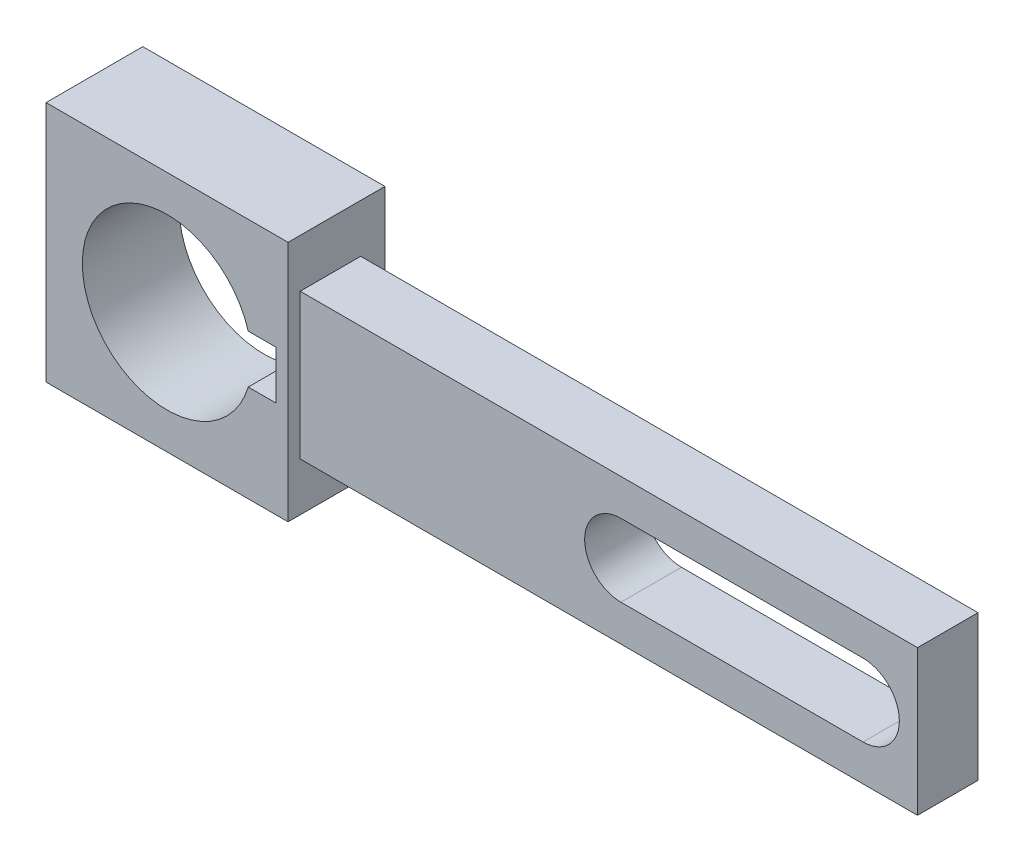
SolidWorks part; units mm, degrees
ref_plane "前视基准面" through (0, 0, 0) normal (0, 0, 1) x (1, 0, 0)
ref_plane "上视基准面" through (0, 0, 0) normal (0, 1, 0) x (1, 0, 0)
ref_plane "右视基准面" through (0, 0, 0) normal (1, 0, 0) x (0, 0, -1)
sketch "草图1" plane through (0, 0, 0) normal (0, 0, 1) x (1, 0, 0)
  line L0 (5, 2) -> (7, 0) construction
  line L9 (-10, -10) -> (10, -10)
  line L10 (-10, -10) -> (-10, 10)
  line L11 (-10, 10) -> (10, 10)
  line L12 (10, -10) -> (10, 10)
  line L13 (-10, -10) -> (10, 10) construction
  line L14 (-10, 10) -> (10, -10) construction
  line L15 (6.7082, -2) -> (9, -2)
  line L16 (5, -2) -> (5, 2) construction
  line L17 (6.7082, 2) -> (9, 2)
  line L18 (9, -2) -> (9, 2)
  line L19 (7, 0) -> (9, 2) construction
  line L20 (7, 0) -> (9, -2) construction
  line L21 (5, 2) -> (6.7082, 2) construction
  line L22 (5, -2) -> (7, 0) construction
  line L23 (5, -2) -> (6.7082, -2) construction
  arc A1 (6.7082, 2) -> (6.7082, -2) centre (0, 0) ccw
  arc A2 (7, 0) -> (6.7082, 2) centre (0, 0) ccw construction
  arc A3 (6.7082, -2) -> (7, 0) centre (0, 0) ccw construction
  point P7 (7, 0)
  dimension "D1" = 14
  dimension "D2" = 20
  dimension "D3" = 20
  dimension "D4" = 2
  dimension "D5" = 4
extrude "凸台-拉伸2" add sketch "草图1" along normal blind 8
sketch "草图2" plane through (10, 0, 0) normal (1, 0, 0) x (0, 0, -1)
  line L0 (-8, -10) -> (-8, 10) construction
  line L1 (-7, 6) -> (-2, 6)
  line L2 (-7, 6) -> (-7, -6)
  line L3 (-7, -6) -> (-2, -6)
  line L4 (-2, 6) -> (-2, -6)
  line L5 (-16.2674, 0) -> (9.7559, 0) construction
  line L6 (-7, 0) -> (-2, 0) construction
  dimension "D1" = 1
  dimension "D2" = 5
  dimension "D3" = 12
  dimension "D4" = 0
extrude "凸台-拉伸3" add sketch "草图2" along normal blind 51
sketch "草图3" plane through (0, 0, 2) normal (0, 0, -1) x (-1, 0, 0)
  line L0 (-56.5, 0) -> (-36.5, 0) construction
  line L1 (-56.5, 3) -> (-36.5, 3)
  line L2 (-56.5, -3) -> (-36.5, -3)
  line L3 (-61, -6) -> (-61, 6) construction
  arc A0 (-56.5, 3) -> (-56.5, -3) centre (-56.5, 0) ccw
  arc A1 (-36.5, -3) -> (-36.5, 3) centre (-36.5, 0) ccw
  point P3 (-46.5, 0)
  point P10 (-61, 0)
  dimension "D1" = 3
  dimension "D2" = 4.5
  dimension "D3" = 20
extrude "切除-拉伸1" cut sketch "草图3" against normal through all
